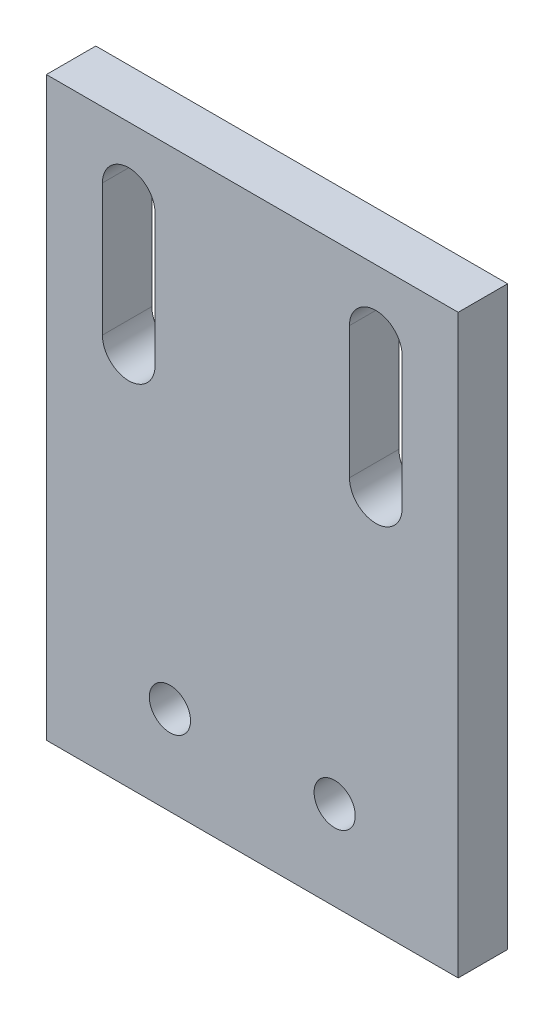
SolidWorks part; units mm, degrees
ref_plane "Front Plane" through (0, 0, 0) normal (0, 0, 1) x (1, 0, 0)
ref_plane "Top Plane" through (0, 0, 0) normal (0, 1, 0) x (1, 0, 0)
ref_plane "Right Plane" through (0, 0, 0) normal (1, 0, 0) x (0, 0, -1)
sketch "草图1" plane through (0, 0, 0) normal (0, 0, 1) x (1, 0, 0)
  line L1 (110.0316, -1.8971) -> (135.0316, -1.8971)
  line L2 (110.0316, -1.8971) -> (110.0316, 33.1029)
  line L3 (110.0316, 33.1029) -> (135.0316, 33.1029)
  line L4 (135.0316, -1.8971) -> (135.0316, 33.1029)
  dimension "D1" = 25
  dimension "D2" = 35
extrude "凸台-拉伸1" add sketch "草图1" along normal blind 3
hole_wizard "M3x0.5 螺纹孔1" positions "草图3" profile "草图2" tap size "M3x0.5" standard "Ansi Metric" end condition through all
sketch "草图3" plane through (0, 0, 3) normal (0, 0, 1) x (1, 0, 0)
  point P0 (117.5316, 3.5)
  point P3 (127.5316, 3.5)
sketch "草图2" plane through (117.5316, 3.5, 3) normal (1, 0, 0) x (0, -1, 0)
  line L0 (0, 0) -> (0, 3)
  line L1 (0, 3) -> (1.25, 3)
  line L2 (1.25, 3) -> (1.25, 0)
  line L5 (1.25, 0) -> (0, 0)
  line L11 (0, -6.35) -> (0, 107.95) construction
  dimension "通孔螺纹孔钻头直径" = 2.5
  dimension "通孔螺纹孔钻头深度" = 3
cosmetic thread "孔螺蚊线1" parameters "D2"=3
cosmetic thread "孔螺蚊线2" parameters "D2"=3
sketch "草图4" plane through (0, 0, 3) normal (0, 0, 1) x (1, 0, 0)
  line L0 (115.0316, 29.1029) -> (115.0316, 21.1029) construction
  line L1 (116.6316, 29.1029) -> (116.6316, 21.1029)
  line L2 (113.4316, 29.1029) -> (113.4316, 21.1029)
  line L3 (130.0316, 29.1029) -> (130.0316, 21.1029) construction
  line L4 (131.6316, 29.1029) -> (131.6316, 21.1029)
  line L5 (128.4316, 29.1029) -> (128.4316, 21.1029)
  line L6 (135.0316, 33.1029) -> (110.0316, 33.1029) construction
  line L7 (110.0316, 33.1029) -> (110.0316, -1.8971) construction
  line L8 (135.0316, -1.8971) -> (135.0316, 33.1029) construction
  arc A0 (116.6316, 29.1029) -> (113.4316, 29.1029) centre (115.0316, 29.1029) ccw
  arc A1 (113.4316, 21.1029) -> (116.6316, 21.1029) centre (115.0316, 21.1029) ccw
  arc A2 (131.6316, 29.1029) -> (128.4316, 29.1029) centre (130.0316, 29.1029) ccw
  arc A3 (128.4316, 21.1029) -> (131.6316, 21.1029) centre (130.0316, 21.1029) ccw
  point P2 (115.0316, 25.1029)
  point P7 (130.0316, 25.1029)
  dimension "D1" = 1.6
  dimension "D2" = 1.6
  dimension "D5" = 4
  dimension "D6" = 4
  dimension "D7" = 5
  dimension "D8" = 5
  dimension "D3" = 8
  dimension "D4" = 8
extrude "切除-拉伸1" cut sketch "草图4" against normal through all
